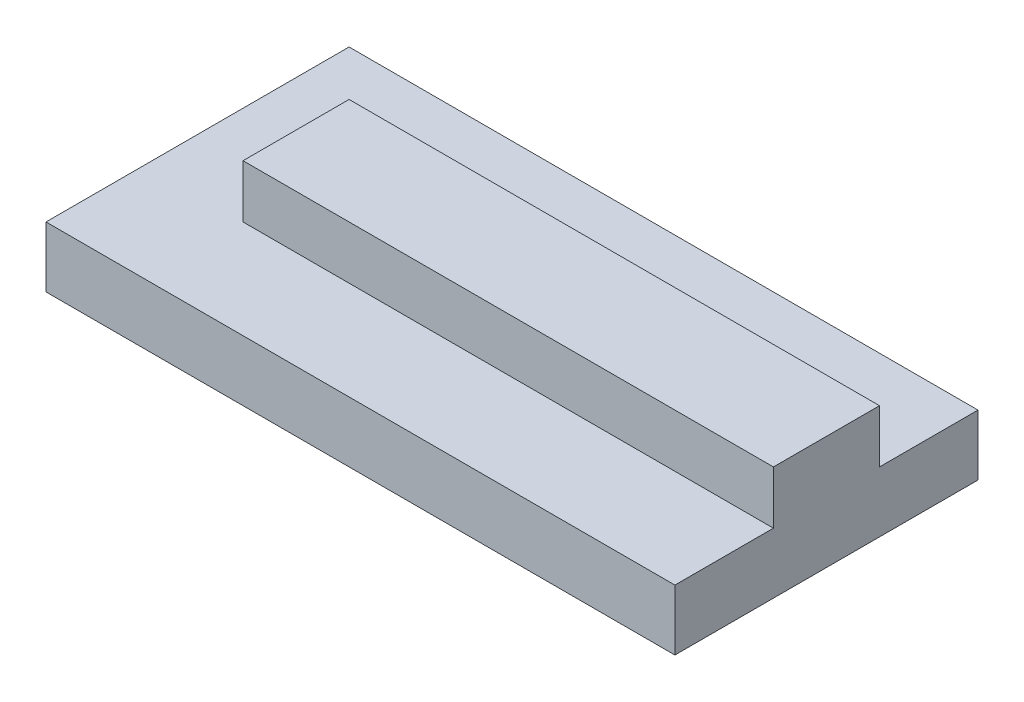
SolidWorks part; units mm, degrees
ref_plane "Front Plane" through (0, 0, 0) normal (0, 0, 1) x (1, 0, 0)
ref_plane "Top Plane" through (0, 0, 0) normal (0, 1, 0) x (1, 0, 0)
ref_plane "Right Plane" through (0, 0, 0) normal (1, 0, 0) x (0, 0, -1)
sketch "Sketch1" plane through (0, 0, 0) normal (0, 1, 0) x (1, 0, 0)
  line L1 (0, 0) -> (41.5, 0)
  line L2 (0, 0) -> (0, 20)
  line L3 (0, 20) -> (41.5, 20)
  line L4 (41.5, 0) -> (41.5, 20)
  dimension "D1" = 41.5
  dimension "D2" = 20
extrude "Boss-Extrude1" add sketch "Sketch1" along normal blind 4
sketch "Sketch2" plane through (0, 4, 0) normal (0, 1, 0) x (1, 0, 0)
  line L0 (6.5, 6.5) -> (6.5, 0) construction
  line L1 (6.5, 6.5) -> (41.5, 6.5)
  line L2 (6.5, 6.5) -> (6.5, 13.5)
  line L3 (6.5, 13.5) -> (41.5, 13.5)
  line L4 (41.5, 6.5) -> (41.5, 13.5)
  line L5 (0, 0) -> (41.5, 0) construction
  line L6 (6.5, 6.5) -> (0, 6.5) construction
  line L7 (6.5, 13.5) -> (6.5, 20) construction
  line L8 (41.5, 20) -> (0, 20) construction
  line L9 (6.5, 13.5) -> (0, 13.5) construction
  line L10 (0, 20) -> (0, 0) construction
  line L11 (41.5, 0) -> (41.5, 20) construction
  dimension "D1" = 6.5
extrude "Boss-Extrude2" add sketch "Sketch2" along normal blind 3.5
